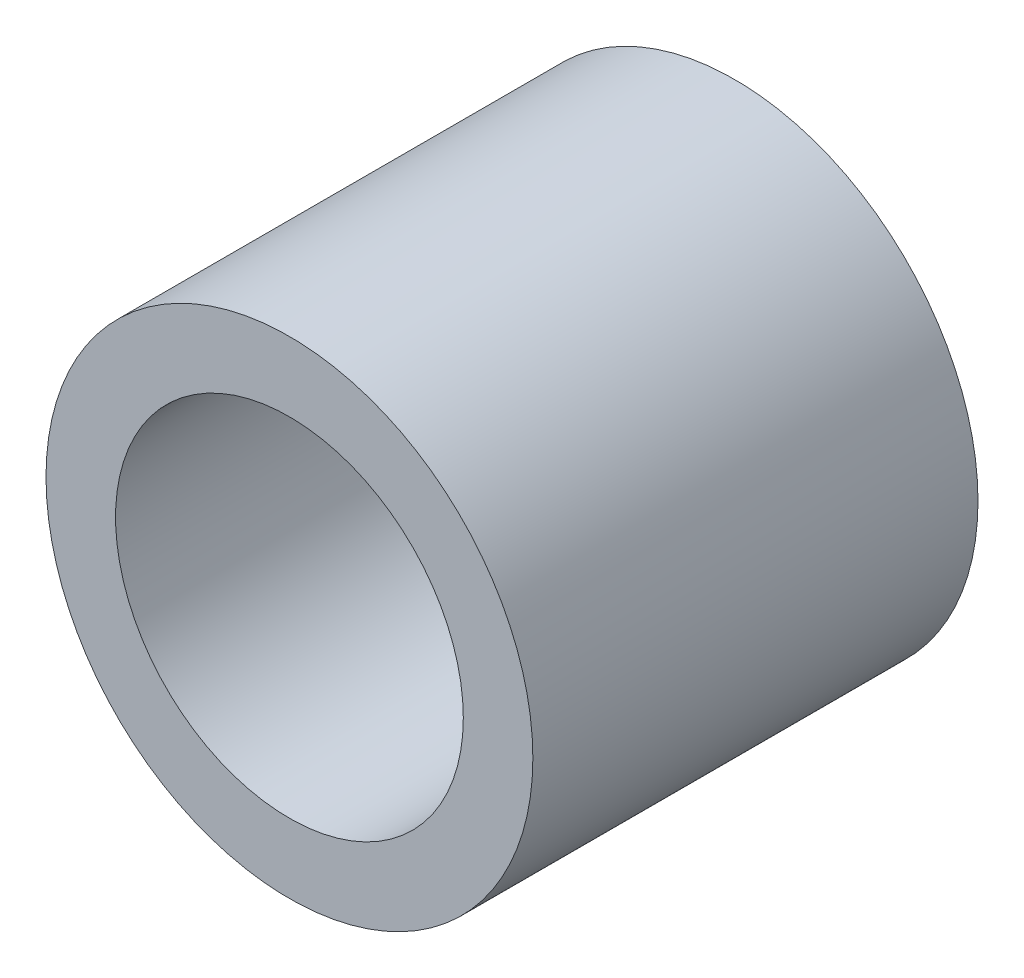
SolidWorks part; units mm, degrees
ref_plane "Front Plane" through (0, 0, 0) normal (1, 0, 0) x (0, 1, 0)
ref_plane "Top Plane" through (0, 0, 0) normal (0, 0, 1) x (0, 1, 0)
ref_plane "Right Plane" through (0, 0, 0) normal (0, 1, 0) x (-1, 0, 0)
sketch "Sketch1" plane through (0, 0, 0) normal (0, 0, 1) x (0, 1, 0)
  circle A0 centre (0, 0) radius 7.9375
  circle A1 centre (0, 0) radius 11.1125
  dimension "D1" = 15.875
  dimension "D2" = 3.175
extrude "Boss-Extrude1" add sketch "Sketch1" along normal blind 20.32
